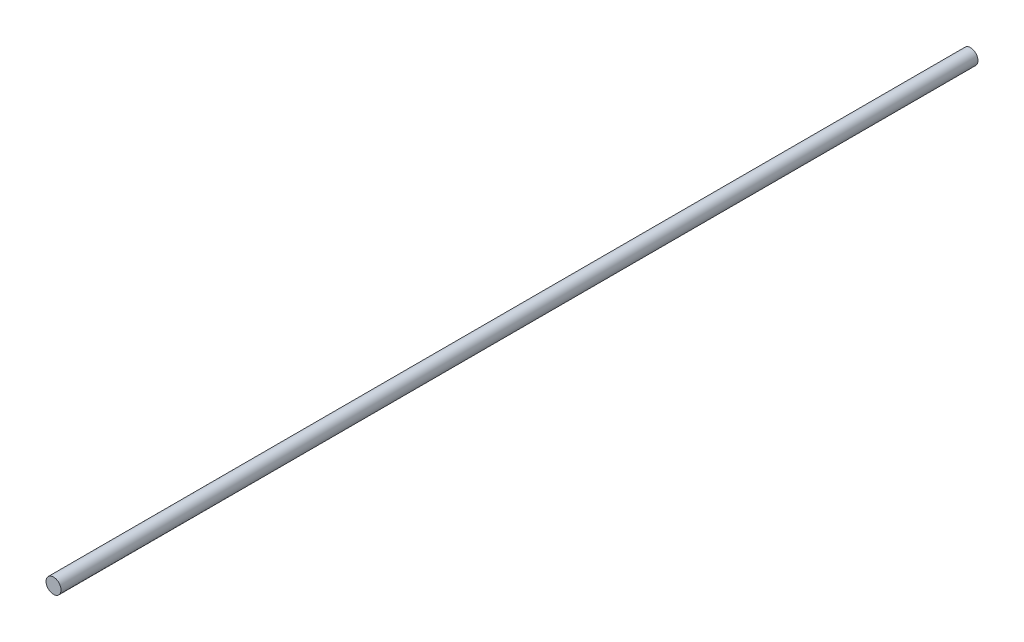
SolidWorks part; units mm, degrees
ref_plane "Plan de face" through (0, 0, 0) normal (0, 0, 1) x (1, 0, 0)
ref_plane "Plan de dessus" through (0, 0, 0) normal (0, 1, 0) x (1, 0, 0)
ref_plane "Plan de droite" through (0, 0, 0) normal (1, 0, 0) x (0, 0, -1)
sketch "Esquisse1" plane through (0, 0, 0) normal (0, 0, 1) x (1, 0, 0)
  circle A0 centre (0, 0) radius 5
  dimension "D1" = 10
extrude "Boss.-Extru.1" add sketch "Esquisse1" along normal blind 610
